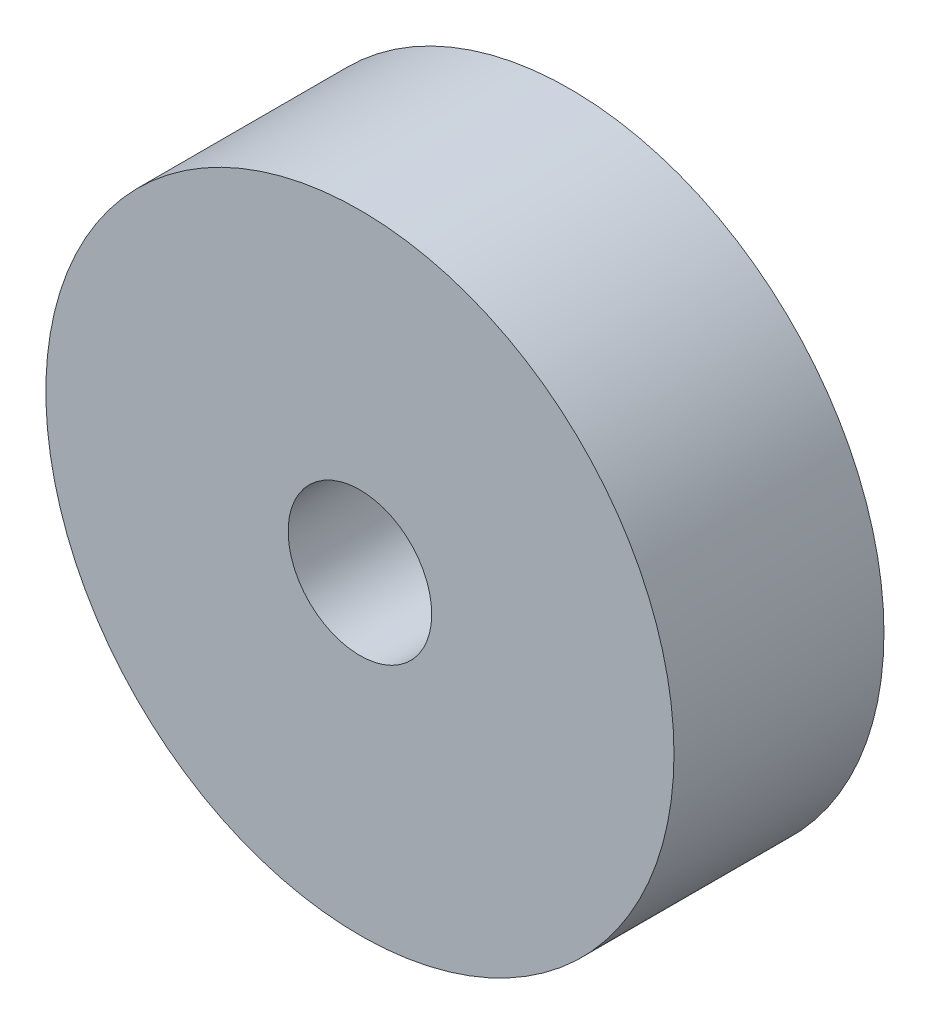
SolidWorks part; units mm, degrees
ref_plane "Alzado" through (0, 0, 0) normal (0, 0, 1) x (1, 0, 0)
ref_plane "Planta" through (0, 0, 0) normal (0, 1, 0) x (1, 0, 0)
ref_plane "Vista lateral" through (0, 0, 0) normal (1, 0, 0) x (0, 0, -1)
sketch "Croquis1" plane through (0, 0, 0) normal (0, 0, 1) x (1, 0, 0)
  circle A0 centre (0, 0) radius 17.5
  circle A1 centre (0, 0) radius 4
  dimension "D1" = 35
  dimension "D2" = 8
extrude "Saliente-Extruir1" add sketch "Croquis1" along normal mid plane 11.7
